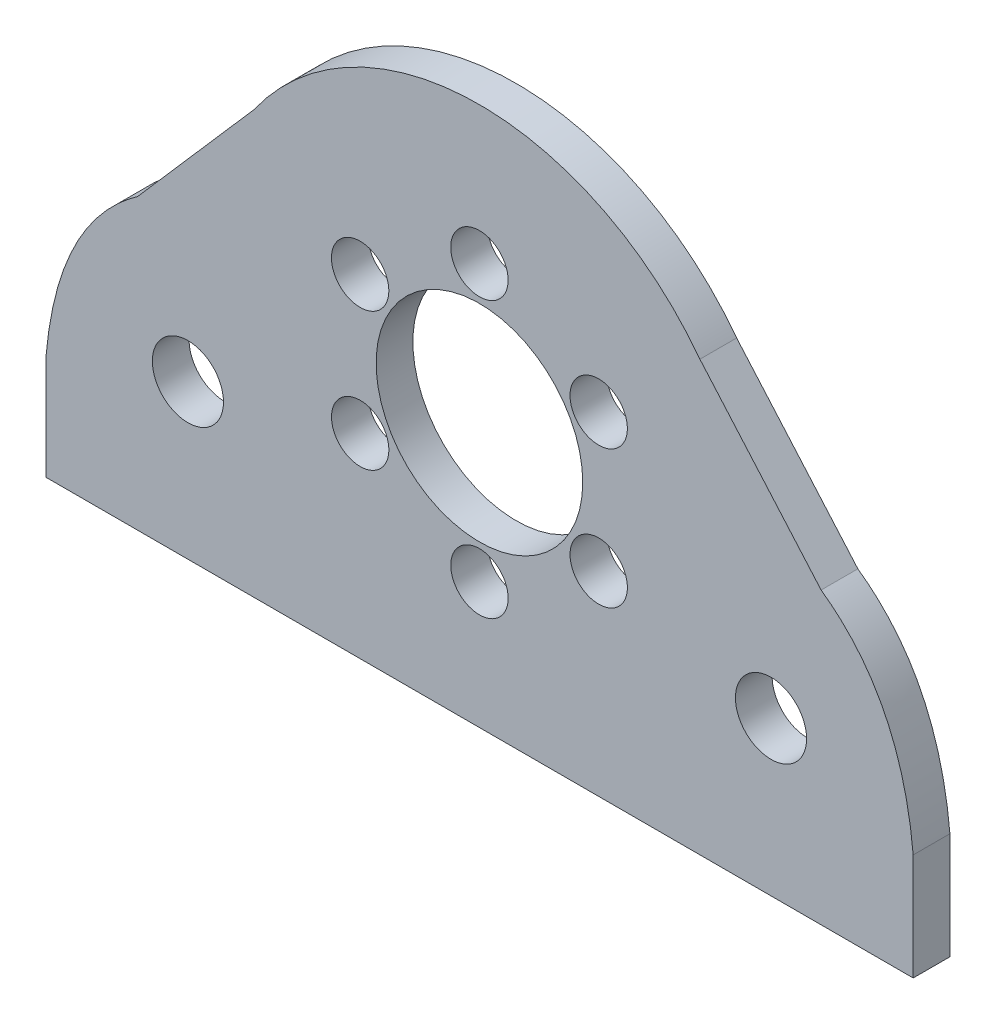
SolidWorks part; units mm, degrees
ref_plane "Alzado" through (0, 0, 0) normal (0, 0, 1) x (1, 0, 0)
ref_plane "Planta" through (0, 0, 0) normal (0, 1, 0) x (1, 0, 0)
ref_plane "Vista lateral" through (0, 0, 0) normal (1, 0, 0) x (0, 0, -1)
sketch "Croquis1" plane through (0, 0, 0) normal (0, 0, 1) x (1, 0, 0)
  line L0 (-18.877, -10.5538) -> (18.8921, -10.5538)
  line L1 (18.8921, -10.5538) -> (18.8921, -5.9109)
  line L2 (-18.877, -10.5538) -> (-18.877, -5.9588)
  line L3 (-14.8866, 2.0361) -> (-9.8168, 7.8494)
  line L4 (14.8814, 2.0739) -> (9.6015, 8.1425)
  line L5 (-0.0012, 0.9462) -> (0, 0) construction
  line L6 (0, 0) -> (0, -1.2315) construction
  circle A8 centre (-0.0012, 0.9462) radius 4.5
  circle A12 centre (-0.0024, 6.945) radius 1.25
  circle A13 centre (5.1933, 3.9466) radius 1.25
  circle A14 centre (5.1945, -2.0522) radius 1.25
  circle A15 centre (0, -5.0526) radius 1.25
  circle A16 centre (-5.1957, -2.0542) radius 1.25
  circle A17 centre (-5.1969, 3.9446) radius 1.25
  circle A19 centre (12.6988, -3.8538) radius 1.55
  circle A20 centre (-12.6988, -3.8538) radius 1.55
  arc A21 (9.6017, 8.1423) -> (-9.8168, 7.8494) centre (-0.0012, 0.9462) ccw
  spline S0 degree 2 poles (-18.877, -5.9588) (-18.3773, -0.439) (-14.8866, 2.0361) knots 0 0 0 0.734097 0.734097 0.734097
  spline S2 degree 2 poles (18.8921, -5.9109) (18.3783, -0.3924) (14.8814, 2.0739) knots 0 0 0 0.734097 0.734097 0.734097
  point P17 (0, 0)
  point P18 (0, 0)
  point P23 (0, 0)
  point P25 (0, 0)
  dimension "D2" = 37.7691
  dimension "D3" = 4.6428
extrude "Saliente-Extruir1" add sketch "Croquis1" along normal blind 1.6
